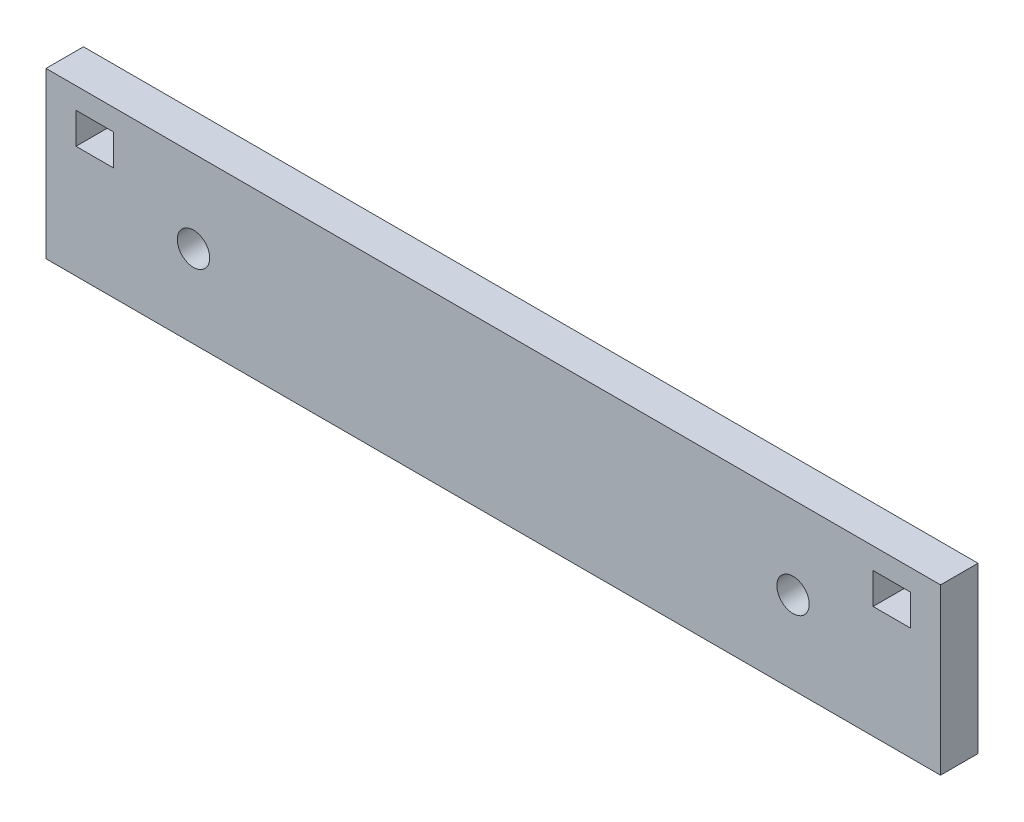
SolidWorks part; units mm, degrees
material "Beech"
ref_plane "Front Plane" through (0, 0, 0) normal (0, 0, 1) x (1, 0, 0)
ref_plane "Top Plane" through (0, 0, 0) normal (0, 1, 0) x (1, 0, 0)
ref_plane "Right Plane" through (0, 0, 0) normal (1, 0, 0) x (0, 0, -1)
sketch "Sketch1" plane through (0, 0, 0) normal (0, 0, 1) x (1, 0, 0)
  line L1 (18.9484, -3.4925) -> (-18.9484, -3.4925)
  line L2 (18.9484, -3.4925) -> (18.9484, 3.4925)
  line L3 (18.9484, 3.4925) -> (-18.9484, 3.4925)
  line L4 (-18.9484, -3.4925) -> (-18.9484, 3.4925)
  line L5 (18.9484, -3.4925) -> (-18.9484, 3.4925) construction
  line L6 (18.9484, 3.4925) -> (-18.9484, -3.4925) construction
  line L12 (0, -1000) -> (0, 49000) construction
  line L13 (-1000, 0) -> (49000, 0) construction
  line L16 (-17.6784, 2.5908) -> (-17.6784, 1.27)
  line L17 (-17.6784, 1.27) -> (-16.0909, 1.27)
  line L35 (-16.0909, 1.27) -> (-16.0909, 2.5908)
  line L36 (-16.0909, 2.5908) -> (-17.6784, 2.5908)
  line L37 (-17.6784, 2.5908) -> (-17.6784, 1.27)
  line L38 (-17.6784, 1.27) -> (-16.0909, 1.27)
  line L39 (-16.0909, 1.27) -> (-16.0909, 2.5908)
  line L40 (-16.0909, 2.5908) -> (-17.6784, 2.5908)
  line L41 (16.0909, 2.5908) -> (16.0909, 1.27)
  line L42 (16.0909, 1.27) -> (17.6784, 1.27)
  line L43 (17.6784, 1.27) -> (17.6784, 2.5908)
  line L44 (17.6784, 2.5908) -> (16.0909, 2.5908)
  line L45 (16.0909, 2.5908) -> (16.0909, 1.27)
  line L46 (16.0909, 1.27) -> (17.6784, 1.27)
  line L47 (17.6784, 1.27) -> (17.6784, 2.5908)
  line L48 (17.6784, 2.5908) -> (16.0909, 2.5908)
  circle A0 centre (-12.7, 0) radius 0.6858
  circle A1 centre (12.7, 0) radius 0.6858
  point P0 (0, 0)
  dimension "D6" = 12.7
  dimension "D5" = 1.3716
  dimension "D1" = 6.985
  dimension "D2" = 0
  dimension "D3" = 1.27
  dimension "D4" = 0
extrude "Boss-Extrude1" add sketch "Sketch1" along normal blind 1.5875
